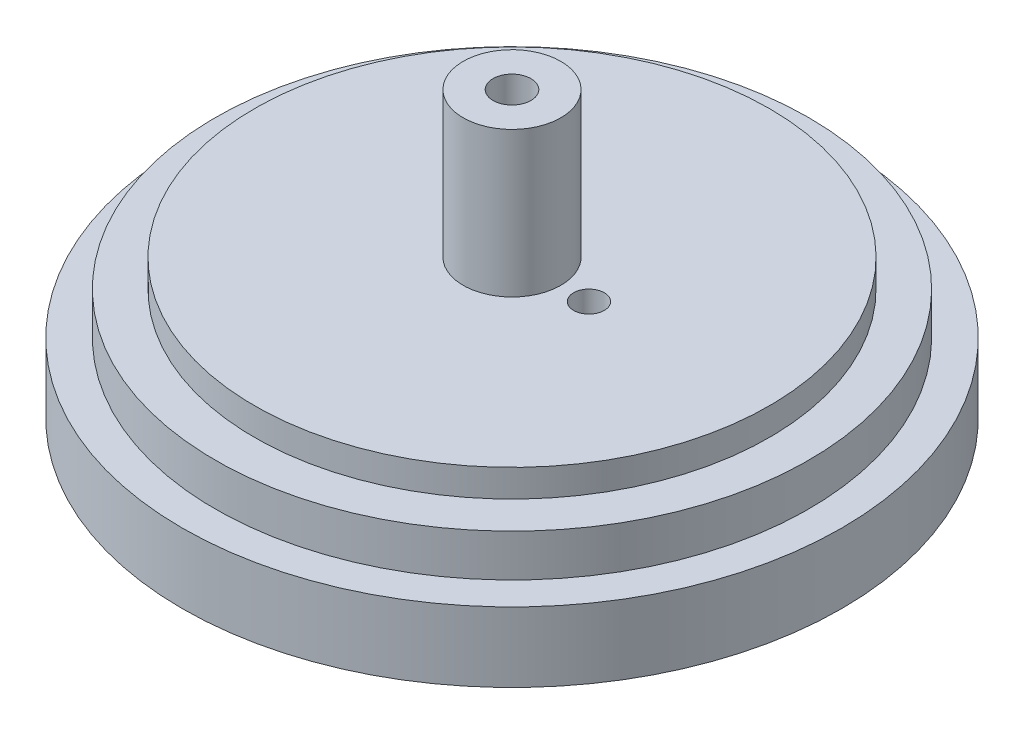
SolidWorks part; units mm, degrees
material "ABS"
ref_plane "Front" through (0, 0, 0) normal (0, 0, 1) x (1, 0, 0)
ref_plane "Top" through (0, 0, 0) normal (0, 1, 0) x (1, 0, 0)
ref_plane "Right" through (0, 0, 0) normal (1, 0, 0) x (0, 0, -1)
sketch "Sketch1" plane through (0, 0, 0) normal (0, 0, 1) x (1, 0, 0)
  line L0 (0, 0) -> (-23.425, 0)
  line L1 (-23.425, 0) -> (-23.425, -2.5)
  line L3 (-30, -6.35) -> (-30, -12.7)
  line L4 (-30, -12.7) -> (0, -12.7)
  line L5 (0, -12.7) -> (0, 0)
  line L6 (0, 0) -> (0, -12.7) construction
  line L7 (-30, -6.35) -> (-27, -6.35)
  line L8 (-27, -6.35) -> (-27, -2.5)
  line L9 (-27, -2.5) -> (-23.425, -2.5)
  line L10 (0, -12.7) -> (0, -19.7735) construction
  dimension "D1" = 54
  dimension "D2" = 12.7
  dimension "D3" = 2.5
  dimension "D4" = 30
  dimension "D5" = 6.35
  dimension "D6" = 23.425
revolve "Revolve1" add sketch "Sketch1" angle 360 about L5
sketch "Sketch3" plane through (0, 0, 0) normal (0, -1, 0) x (1, 0, 0)
  line L0 (7, 0) -> (0, 0) construction
  circle A0 centre (7, 0) radius 1.397
  dimension "D1" = 2.794
  dimension "D2" = 7
extrude "Cut-Extrude2" cut sketch "Sketch3" along normal up to next
sketch "Sketch12" plane through (0, 0, 0) normal (0, 1, 0) x (1, 0, 0)
  circle A0 centre (0, 0) radius 4.445
  dimension "D1" = 8.89
extrude "Boss-Extrude1" add sketch "Sketch12" along normal blind 13.208
hole_wizard "#4 Clearance Hole1" positions "Sketch13" profile "Sketch14" hole size "#4" standard "ANSI Inch" end condition through all
sketch "Sketch13" plane through (0, 13.208, 0) normal (0, 1, 0) x (1, 0, 0)
  point P0 (0, 0)
sketch "Sketch14" plane through (0, 13.208, 0) normal (1, 0, 0) x (0, 0, 1)
  line L0 (0, 0) -> (0, 25.908)
  line L1 (0, 25.908) -> (1.7272, 25.908)
  line L2 (1.7272, 25.908) -> (1.7272, 0)
  line L5 (1.7272, 0) -> (0, 0)
  line L11 (0, -6.35) -> (0, 107.95) construction
  dimension "Thru Hole Dia." = 3.4544
  dimension "Thru Hole Depth" = 25.908
sketch "Sketch15" plane through (0, -12.7, 0) normal (0, -1, 0) x (-1, 0, 0)
  line L0 (0, 0) -> (0, -3.8128) construction
  line L1 (0, -3.8128) -> (3.302, -1.9064)
  line L2 (3.302, -1.9064) -> (3.302, 1.9064)
  line L3 (3.302, 1.9064) -> (0, 3.8128)
  line L4 (0, 3.8128) -> (-3.302, 1.9064)
  line L5 (-3.302, 1.9064) -> (-3.302, -1.9064)
  line L6 (-3.302, -1.9064) -> (0, -3.8128)
  line L8 (0, -3.6662) -> (3.175, -1.8331) construction
  line L9 (3.175, -1.8331) -> (3.175, 1.8331) construction
  line L10 (3.175, 1.8331) -> (0, 3.6662) construction
  line L11 (0, 3.6662) -> (-3.175, 1.8331) construction
  line L12 (-3.175, 1.8331) -> (-3.175, -1.8331) construction
  line L13 (-3.175, -1.8331) -> (0, -3.6662) construction
  circle A0 centre (0, 0) radius 3.302 construction
  circle A1 centre (0, 0) radius 3.175 construction
  dimension "D1" = 6.604
  dimension "D2" = 6.35
extrude "Cut-Extrude3" cut sketch "Sketch15" against normal blind 8.5
